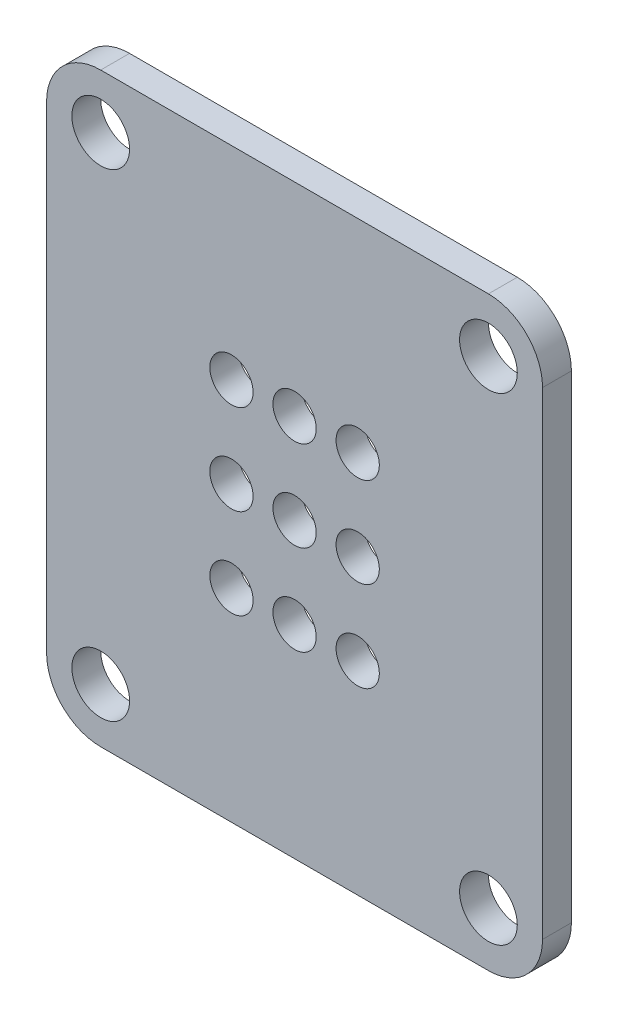
SolidWorks part; units mm, degrees
ref_plane "Front Plane" through (0, 0, 0) normal (0, 0, 1) x (1, 0, 0)
ref_plane "Top Plane" through (0, 0, 0) normal (0, 1, 0) x (1, 0, 0)
ref_plane "Right Plane" through (0, 0, 0) normal (1, 0, 0) x (0, 0, -1)
sketch "Sketch1" plane through (0, 0, 0) normal (0, 0, 1) x (1, 0, 0)
  line L0 (-10.75, -13.25) -> (10.75, 13.25) construction
  line L1 (-13.0797, -11.3599) -> (8.4203, 15.1401)
  line L2 (-8.4203, -15.1401) -> (13.0797, 11.3599)
  line L3 (0, 0) -> (0, 12.5) construction
  line L4 (-10.75, 13.25) -> (10.75, -13.25) construction
  line L5 (-8.4203, 15.1401) -> (13.0797, -11.3599)
  line L6 (-13.0797, 11.3599) -> (8.4203, -15.1401)
  line L7 (-10.75, 16.25) -> (10.75, 16.25)
  line L8 (-10.75, -16.25) -> (10.75, -16.25)
  line L9 (10.75, 16.25) -> (10.75, 13.25) construction
  line L10 (10.75, 13.25) -> (13.0797, 11.3599) construction
  line L11 (-9.975, 7.5332) -> (0, 0) construction
  line L12 (0, 0) -> (-9.975, -7.5332) construction
  line L13 (13.75, 13.25) -> (13.75, -13.25)
  line L14 (0, -55) -> (0, 55) construction
  line L15 (-13.75, 13.25) -> (-13.75, -13.25)
  circle A0 centre (0, 0) radius 12.5
  arc A1 (-13.0797, -11.3599) -> (-8.4203, -15.1401) centre (-10.75, -13.25) ccw
  arc A2 (13.0797, 11.3599) -> (8.4203, 15.1401) centre (10.75, 13.25) ccw
  arc A3 (-8.4203, 15.1401) -> (-13.0797, 11.3599) centre (-10.75, 13.25) ccw
  arc A4 (8.4203, -15.1401) -> (13.0797, -11.3599) centre (10.75, -13.25) ccw
  point P5 (0, 0)
  point P15 (0, 0)
  point P20 (0, 0)
  point P23 (-9.975, 7.5332)
  point P31 (10.75, 13.25)
  dimension "D1" = 25
  dimension "D3" = 3
  dimension "D6" = 129.053
  dimension "D2" = 21.5
  dimension "D4" = 13.25
  dimension "D7" = 11.3599
  dimension "D8" = 13.0797
  dimension "D9" = 74.121
  dimension "D5" = 2
extrude "Boss-Extrude1" add sketch "Sketch1" along normal mid plane 1.6 contours L2 A2 L1 A0 | L6 A4 L5 A0 | L1 A1 L2 A0 | A3 L5 A0 L1 A2 L7 | A4 L6 A0 L2 A1 L8 | L5 A3 L6 A0 | A3 L15 A1 L1 A0 L6 | A4 L13 A2 L2 A0 L5
sketch "Sketch4" plane through (0, 0, 0.8) normal (0, 0, 1) x (1, 0, 0)
  circle A0 centre (10.75, 13.25) radius 1.6
  circle A1 centre (10.75, -13.25) radius 1.6
  circle A2 centre (-10.75, -13.25) radius 1.6
  circle A3 centre (-10.75, 13.25) radius 1.6
  arc A4 (-10.75, 16.25) -> (-13.75, 13.25) centre (-10.75, 13.25) ccw construction
  arc A5 (-13.75, -13.25) -> (-10.75, -16.25) centre (-10.75, -13.25) ccw construction
  arc A6 (10.75, -16.25) -> (13.75, -13.25) centre (10.75, -13.25) ccw construction
  point P12 (0, 0)
  dimension "D2" = 3.2
extrude "Cut-Extrude3" cut sketch "Sketch4" against normal through all
sketch "Sketch5" plane through (0, 0, 0.8) normal (0, 0, 1) x (1, 0, 0)
  circle A0 centre (3.5, -5) radius 1.2
  circle A1 centre (0, -5) radius 1.2
  circle A2 centre (-3.5, -5) radius 1.2
  circle A3 centre (3.5, 5) radius 1.2
  circle A4 centre (0, 5) radius 1.2
  circle A5 centre (-3.5, 5) radius 1.2
  circle A6 centre (-3.5, 0) radius 1.2
  circle A7 centre (0, 0) radius 1.2
  circle A8 centre (3.5, 0) radius 1.2
  dimension "D1" = 2.4
extrude "Cut-Extrude4" cut sketch "Sketch5" against normal through all
